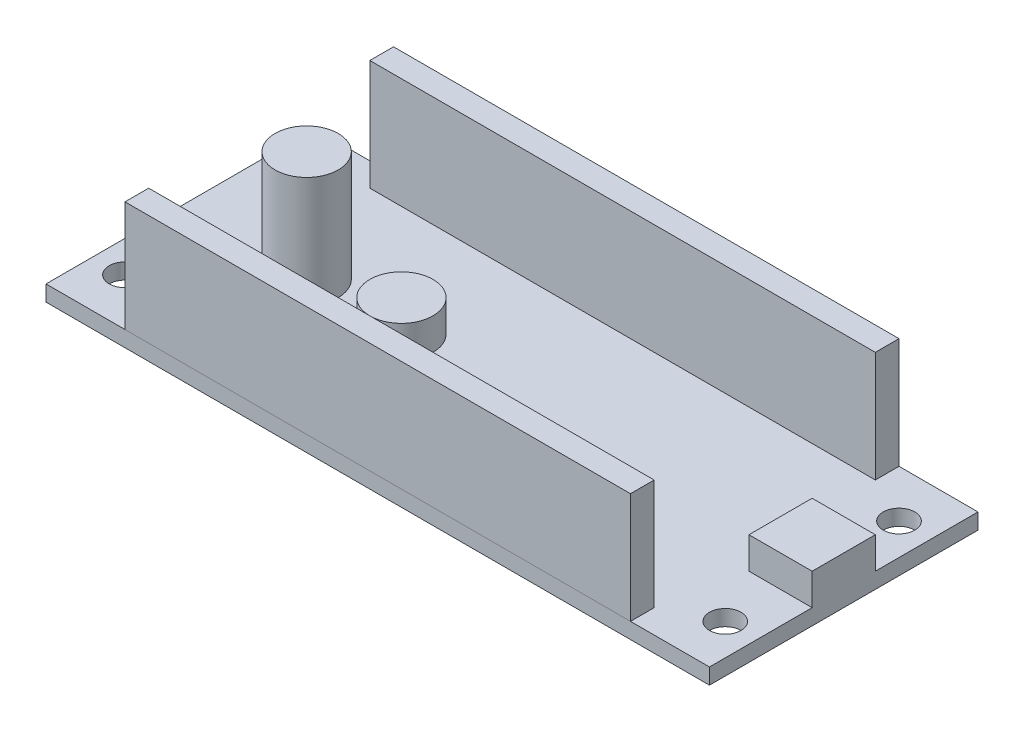
SolidWorks part; units mm, degrees
ref_plane "Front Plane" through (0, 0, 0) normal (0, 0, 1) x (1, 0, 0)
ref_plane "Top Plane" through (0, 0, 0) normal (0, 1, 0) x (1, 0, 0)
ref_plane "Right Plane" through (0, 0, 0) normal (1, 0, 0) x (0, 0, -1)
sketch "Sketch1" plane through (0, 0, 0) normal (0, 1, 0) x (1, 0, 0)
  line L1 (-33.3375, 13.4938) -> (33.3375, 13.4938)
  line L2 (-33.3375, 13.4938) -> (-33.3375, -13.4937)
  line L3 (-33.3375, -13.4937) -> (33.3375, -13.4937)
  line L4 (33.3375, 13.4938) -> (33.3375, -13.4937)
  line L5 (-33.3375, 13.4938) -> (33.3375, -13.4937) construction
  line L6 (-33.3375, -13.4937) -> (33.3375, 13.4938) construction
  point P0 (0, 0)
  dimension "D1" = 66.675
  dimension "D2" = 26.9875
extrude "Boss-Extrude1" add sketch "Sketch1" along normal blind 1.5875
sketch "Sketch2" plane through (0, 1.5875, 0) normal (0, 1, 0) x (1, 0, 0)
  line L0 (33.3375, 13.4938) -> (-33.3375, 13.4938) construction
  line L1 (-25.4, 13.4938) -> (25.4, 13.4938)
  line L2 (-25.4, 13.4938) -> (-25.4, 11.1125)
  line L3 (-25.4, 11.1125) -> (25.4, 11.1125)
  line L4 (25.4, 13.4938) -> (25.4, 11.1125)
  line L5 (-33.3375, -13.4937) -> (33.3375, -13.4937) construction
  line L6 (-25.4, -13.4937) -> (25.4, -13.4937)
  line L7 (-25.4, -13.4937) -> (-25.4, -11.1125)
  line L8 (-25.4, -11.1125) -> (25.4, -11.1125)
  line L9 (25.4, -13.4937) -> (25.4, -11.1125)
  line L10 (-33.3375, 13.4938) -> (-33.3375, -13.4937) construction
  circle A0 centre (-20.6375, 0) radius 3.175
  point P12 (0, 11.1125)
  point P13 (0, -11.1125)
  dimension "D4" = 6.35
  dimension "D1" = 2.3813
  dimension "D2" = 50.8
  dimension "D3" = 12.7
extrude "Boss-Extrude2" add sketch "Sketch2" along normal blind 11.1125 separate body
sketch "Sketch3" plane through (0, 1.5875, 0) normal (0, 1, 0) x (1, 0, 0)
  line L0 (33.3375, -13.4937) -> (33.3375, 13.4938) construction
  line L1 (33.3375, 3.175) -> (26.9875, 3.175)
  line L2 (33.3375, 3.175) -> (33.3375, -3.175)
  line L3 (33.3375, -3.175) -> (26.9875, -3.175)
  line L4 (26.9875, 3.175) -> (26.9875, -3.175)
  circle A0 centre (-11.1125, 0) radius 3.175
  circle A1 centre (-20.6375, 0) radius 3.175 construction
  point P6 (26.9875, 0)
  dimension "D3" = 6.35
  dimension "D4" = 9.525
  dimension "D1" = 6.35
  dimension "D2" = 6.35
extrude "Boss-Extrude3" add sketch "Sketch3" along normal blind 3.175
sketch "Sketch4" plane through (0, 1.5875, 0) normal (0, 1, 0) x (1, 0, 0)
  line L0 (-33.3375, -13.4937) -> (33.3375, -13.4937) construction
  line L1 (-33.3375, 13.4938) -> (-33.3375, -13.4937) construction
  line L2 (33.3375, 13.4938) -> (-33.3375, 13.4938) construction
  line L3 (33.3375, 3.175) -> (33.3375, 13.4938) construction
  circle A0 centre (30.1625, -8.7312) radius 1.5875
  circle A1 centre (30.1625, 8.7313) radius 1.5875
  circle A2 centre (-30.1625, 8.7313) radius 1.5875
  circle A3 centre (-30.1625, -8.7312) radius 1.5875
  dimension "D5" = 3.175
  dimension "D1" = 4.7625
  dimension "D2" = 3.175
  dimension "D3" = 4.7625
  dimension "D4" = 3.175
extrude "Cut-Extrude1" cut sketch "Sketch4" against normal through all
sketch "Sketch5" plane through (0, 1.5875, 0) normal (0, 1, 0) x (1, 0, 0)
  line L0 (11.9602, 13.4938) -> (11.9602, -13.4937) construction
  line L2 (-25.4, -13.4937) -> (25.4, -13.4937) construction
  line L3 (25.4, 13.4938) -> (-25.4, 13.4938) construction
  text T0 "OpenCM9.04" font "Century Gothic" height 3.5
